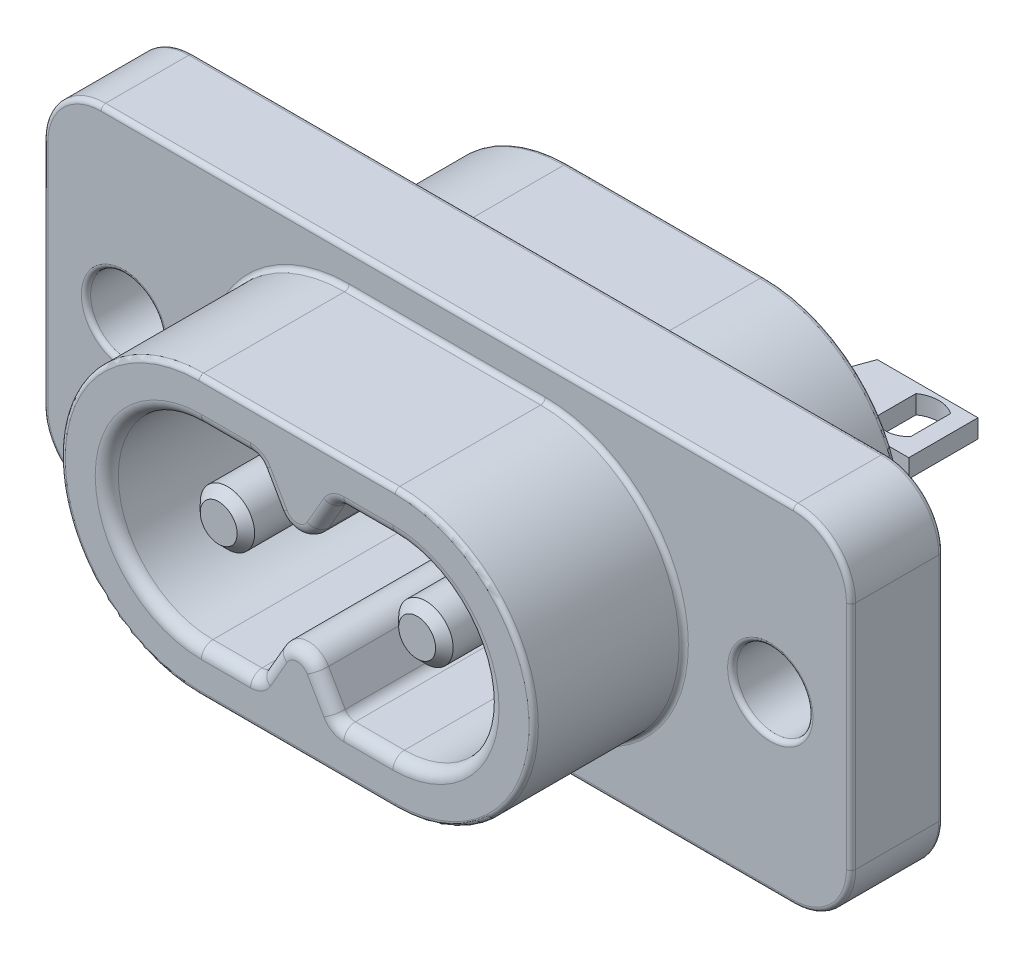
SolidWorks part; units mm, degrees
material "ABS_Black"
ref_plane "Přední rovina" through (0, 0, 0) normal (0, 0, 1) x (1, 0, 0)
ref_plane "Horní rovina" through (0, 0, 0) normal (0, 1, 0) x (1, 0, 0)
ref_plane "Pravá rovina" through (0, 0, 0) normal (1, 0, 0) x (0, 0, -1)
ref_plane "Rovina1" through (0, 0, -9.5) normal (0, 0, -1) x (-1, 0, 0)
sketch "Skica1" plane through (0, 0, -9.5) normal (0, 0, -1) x (-1, 0, 0)
  line L0 (17.5, 0.8) -> (17.5, 6)
  line L1 (17.5, 6) -> (-17.5, 6)
  line L2 (-17.5, 6) -> (-17.5, 0.8)
  line L3 (-17.5, 0.8) -> (17.5, 0.8)
extrude "Přidat vysunutím1" add sketch "Skica1" against normal blind 9.5
sketch "Skica2" plane through (0, 0.8, 0) normal (0, -1, 0) x (-1, 0, 0)
  line L4 (-9, 11) -> (-9, 14)
  line L8 (-17.5, 0) -> (17.5, 0)
  line L17 (-5.9404, 11) -> (-9, 11)
  line L18 (9, 14) -> (4.6379, 14)
  line L19 (9, 11) -> (9, 14)
  line L20 (5.9404, 11) -> (9, 11)
  line L21 (5.3944, 9.5) -> (5.9404, 11)
  line L22 (17.5, 9.5) -> (5.3944, 9.5)
  line L23 (17.5, 0) -> (17.5, 9.5)
  line L24 (-17.5, 9.5) -> (-17.5, 0)
  line L25 (-5.3944, 9.5) -> (-17.5, 9.5)
  line L26 (-5.9404, 11) -> (-5.3944, 9.5)
  line L27 (-4.6379, 14) -> (-9, 14)
  line L28 (-3, 9.5) -> (-4.6379, 14)
  line L29 (3, 9.5) -> (-3, 9.5)
  line L30 (4.6379, 14) -> (3, 9.5)
extrude "Přidat vysunutím2" add sketch "Skica2" along normal blind 0.8
sketch "Skica3" plane through (0, 0, 0) normal (0, -1, 0) x (1, 0, 0)
  line L0 (-17.5, -9.5) -> (-17.5, 0)
  line L1 (-17.5, 0) -> (17.5, 0)
  line L2 (17.5, 0) -> (17.5, -9.5)
  line L3 (17.5, -9.5) -> (-17.5, -9.5)
extrude "Přidat vysunutím3" add sketch "Skica3" along normal blind 5.3327
sketch "Skica4" plane through (0, 0, -9.5) normal (0, 0, -1) x (-1, 0, 0)
  line L0 (7, -5.3327) -> (17.5, -5.3327)
  line L1 (17.5, -5.3327) -> (17.5, 6)
  line L2 (17.5, 6) -> (4.25, 6)
  arc A0 (4.25, 6) -> (7, -5.3327) centre (4.25, 0) cw
extrude "Odebrat vysunutím1" cut sketch "Skica4" against normal blind 5.5
sketch "Skica5" plane through (0, 0, -9.5) normal (0, 0, -1) x (-1, 0, 0)
  line L0 (-17.5, 6) -> (-17.5, -5.3327)
  line L1 (-17.5, -5.3327) -> (-7, -5.3327)
  line L2 (-4.25, 6) -> (-17.5, 6)
  arc A0 (-7, -5.3327) -> (-4.25, 6) centre (-4.25, 0) cw
extrude "Odebrat vysunutím2" cut sketch "Skica5" against normal blind 5.5
sketch "Skica7" plane through (0, -5.3327, 0) normal (0, -1, 0) x (1, 0, 0)
  line L0 (-7, -9.5) -> (-7, -4)
  line L1 (-7, -4) -> (-17.5, -4)
  line L2 (-17.5, -4) -> (-17.5, 0)
  line L3 (-17.5, 0) -> (17.5, 0)
  line L4 (17.5, 0) -> (17.5, -4)
  line L5 (17.5, -4) -> (7, -4)
  line L6 (7, -4) -> (7, -9.5)
  line L7 (7, -9.5) -> (-7, -9.5)
extrude "Přidat vysunutím4" add sketch "Skica7" along normal blind 2.1673
sketch "Skica9" plane through (0, 6, 0) normal (0, 1, 0) x (1, 0, 0)
  line L0 (-17.5, 0) -> (17.5, 0)
  line L4 (-17.5, 4) -> (-17.5, 0)
  line L5 (17.5, 4) -> (-17.5, 4)
  line L6 (17.5, 0) -> (17.5, 4)
extrude "Přidat vysunutím6" add sketch "Skica9" along normal blind 1.5
sketch "Skica10" plane through (0, 0, -9.5) normal (0, 0, -1) x (-1, 0, 0)
  line L0 (4, -6) -> (7, -6)
  line L1 (7, -6) -> (7, -7.5)
  line L2 (7, -7.5) -> (4, -7.5)
  line L3 (4, -7.5) -> (4, -6)
extrude "Přidat vysunutím7" add sketch "Skica10" along normal blind 2
sketch "Skica11" plane through (0, 0, -9.5) normal (0, 0, -1) x (-1, 0, 0)
  line L0 (-7, -6) -> (-4, -6)
  line L1 (-4, -6) -> (-4, -7.5)
  line L2 (-4, -7.5) -> (-7, -7.5)
  line L3 (-7, -7.5) -> (-7, -6)
extrude "Přidat vysunutím8" add sketch "Skica11" along normal blind 2
ref_plane "Rovina2" through (0, 0, -4) normal (0, 0, 1) x (1, 0, 0)
sketch "Skica13" plane through (0, 0, -4) normal (0, 0, 1) x (1, 0, 0)
  line L0 (-4, -6) -> (-4, -7.5)
  line L1 (-4, -7.5) -> (4, -7.5)
  line L2 (4, -7.5) -> (4, -6)
  line L3 (4, -6) -> (-4, -6)
extrude "Odebrat vysunutím4" cut sketch "Skica13" against normal up to surface up to plane "Rovina1"
sketch "Skica14" plane through (0, -7.5, 0) normal (0, -1, 0) x (1, 0, 0)
  line L0 (-5, -11.5) -> (-5, -10.5)
  line L1 (-6, -10.5) -> (-6, -11.5)
  line L2 (-6, -11.5) -> (-5, -11.5)
  arc A0 (-5, -10.5) -> (-6, -10.5) centre (-5.5, -10.5) ccw
extrude "Odebrat vysunutím5" cut sketch "Skica14" against normal up to next
sketch "Skica15" plane through (0, -6, 0) normal (0, 1, 0) x (-1, 0, 0)
  line L0 (-6, -11.5) -> (-5, -11.5)
  line L1 (-5, -11.5) -> (-5, -10.5)
  line L2 (-6, -10.5) -> (-6, -11.5)
  arc A0 (-5, -10.5) -> (-6, -10.5) centre (-5.5, -10.5) ccw
extrude "Odebrat vysunutím6" cut sketch "Skica15" against normal through all
sketch "Skica16" plane through (0, 0.8, 0) normal (0, 1, 0) x (-1, 0, 0)
  line L0 (-8.25, -11.8386) -> (-8.25, -13.5618)
  line L1 (-6.75, -13.5618) -> (-6.75, -11.8386)
  arc A0 (-8.25, -13.5618) -> (-6.75, -13.5618) centre (-7.5, -12.5) ccw
  arc A1 (-6.75, -11.8386) -> (-8.25, -11.8386) centre (-7.5, -12.5) ccw
extrude "Odebrat vysunutím7" cut sketch "Skica16" against normal through all
sketch "Skica18" plane through (0, 0, 0) normal (0, 0, 1) x (1, 0, 0)
  line L0 (-4.25, 6) -> (4.25, 6)
  line L1 (4.25, -6) -> (-4.25, -6)
  arc A0 (4.25, 6) -> (4.25, -6) centre (4.25, 0) cw
  arc A1 (-4.25, -6) -> (-4.25, 6) centre (-4.25, 0) cw
extrude "Přidat vysunutím9" add sketch "Skica18" along normal blind 6.5
sketch "Skica19" plane through (0, 0, 6.5) normal (0, 0, 1) x (1, 0, 0)
  line L0 (0.866, -2.6) -> (1.7321, -4.1)
  line L1 (1.7321, -4.1) -> (4.15, -4.1)
  line L2 (4.15, 4.1) -> (1.7321, 4.1)
  line L3 (1.7321, 4.1) -> (0.866, 2.6)
  line L4 (-0.866, 2.6) -> (-1.7321, 4.1)
  line L5 (-1.7321, 4.1) -> (-4.15, 4.1)
  line L6 (-4.15, -4.1) -> (-1.7321, -4.1)
  line L7 (-1.7321, -4.1) -> (-0.866, -2.6)
  arc A0 (-0.866, -2.6) -> (0.866, -2.6) centre (0, -3.1) cw
  arc A1 (4.15, -4.1) -> (4.15, 4.1) centre (4.15, 0) ccw
  arc A2 (0.866, 2.6) -> (-0.866, 2.6) centre (0, 3.1) cw
  arc A3 (-4.15, 4.1) -> (-4.15, -4.1) centre (-4.15, 0) ccw
extrude "Odebrat vysunutím9" cut sketch "Skica19" against normal blind 10
sketch "Skica20" plane through (0, 0, 0) normal (0, 1, 0) x (1, 0, 0)
  line L0 (-3.12, 3.5) -> (-4.3, 3.5)
  line L1 (-4.3, 3.5) -> (-4.3, -5.6)
  line L2 (-4.3, -5.6) -> (-3.12, -5.6)
  line L3 (-3.12, -5.6) -> (-3.12, 3.5)
  line L4 (-4.3, 3.5) -> (-4.3, -5.6) construction
revolve "Rotovat1" add sketch "Skica20" angle 360 about L4
sketch "Skica21" plane through (0, 0, 0) normal (0, 1, 0) x (1, 0, 0)
  line L0 (5.48, 3.5) -> (4.3, 3.5)
  line L1 (4.3, 3.5) -> (4.3, -5.6)
  line L2 (4.3, -5.6) -> (5.48, -5.6)
  line L3 (5.48, -5.6) -> (5.48, 3.5)
  line L4 (4.3, 3.5) -> (4.3, -5.6) construction
revolve "Rotovat2" add sketch "Skica21" angle 360 about L4
hole_wizard "Ø3.3 (3.3) průměr díry1" positions "Skica23" profile "Skica22" hole size "Ø3.3" standard "ANSI Metric"
sketch "Skica23" plane through (0, 0, 0) normal (0, 0, 1) x (1, 0, 0)
  point P0 (-14, 0)
  point P1 (14, 0)
sketch "Skica22" plane through (-14, 0, 0) normal (1, 0, 0) x (0, -1, 0)
  line L0 (0, 0) -> (0, 14)
  line L1 (0, 14) -> (1.65, 14)
  line L2 (1.65, 14) -> (1.65, 0)
  line L5 (1.65, 0) -> (0, 0)
  line L11 (0, -6.35) -> (0, 107.95) construction
  dimension "Průměr díry skrz" = 3.3
  dimension "Hloubka díry skrz" = 14
fillet "Zaoblit1" radius 2.5 4 edges at (-17.5, -7.5, -2) (-17.5, 7.5, -2) (17.5, 7.5, -2) (17.5, -7.5, -2)
chamfer "Zkosení1" distance 0.38 angle 45 2 edges at (5.48, 0, 5.6) (-3.12, 0, 5.6)
fillet "Zaoblit3" radius 0.5 16 edges at (-2.941, -4.1, 6.5) (-1.299, -3.35, 6.5) (-8.25, 0, 6.5) (0, -2.1, 6.5) (-2.941, 4.1, 6.5) (1.299, -3.35, 6.5) (-1.299, 3.35, 6.5) (2.941, -4.1, 6.5) (0, 2.1, 6.5) (8.25, 0, 6.5) (1.299, 3.35, 6.5) (2.941, 4.1, 6.5) (-1.7321, 4.1, 1.5) (1.7321, 4.1, 1.5) (-1.7321, -4.1, 1.5) (1.7321, -4.1, 1.5)
pattern_linear "LinPole1" count 2 spacing 15 along (-1, 0, 0) of "Odebrat vysunutím7"
fillet "Zaoblit4" radius 0.2 14 edges at (0, -6, 0) (10.25, 0, 0) (0, 6, 0) (-10.25, 0, 0) (-16.7678, 6.7678, 0) (0, 7.5, 0) (16.7678, 6.7678, 0) (17.5, 0, 0) (16.7678, -6.7678, 0) (0, -7.5, 0) (-16.7678, -6.7678, 0) (-17.5, 0, 0) (15.65, 0, 0) (-12.35, 0, 0)
fillet "Zaoblit5" radius 0.2 4 edges at (10.25, 0, 6.5) (0, -6, 6.5) (-10.25, 0, 6.5) (0, 6, 6.5)
fillet "Zaoblit6" radius 0.2 28 edges at (-4, -7.5, -7.75) (4, -7.5, -7.75) (-7, -7.5, -7.75) (7, -7.5, -7.75) (-10.0808, 1.4149, -9.5) (0, 6, -9.5) (-4, -6.75, -4) (0, -6, -4) (0, -7.5, -4) (4, -6.75, -4) (-7, -6.4163, -4) (-10.0808, 1.4149, -4) (0, 6, -4) (10.0808, 1.4149, -9.5) (10.0808, 1.4149, -4) (7, -6.4163, -4) (11, -7.5, -4) (16.7678, -6.7678, -4) (17.5, 0, -4) (16.7678, 6.7678, -4) (0, 7.5, -4) (-16.7678, 6.7678, -4) (-17.5, 0, -4) (-16.7678, -6.7678, -4) (-11, -7.5, -4) (15.65, 0, -4) (-12.35, 0, -4) (0, -6, -9.5)
